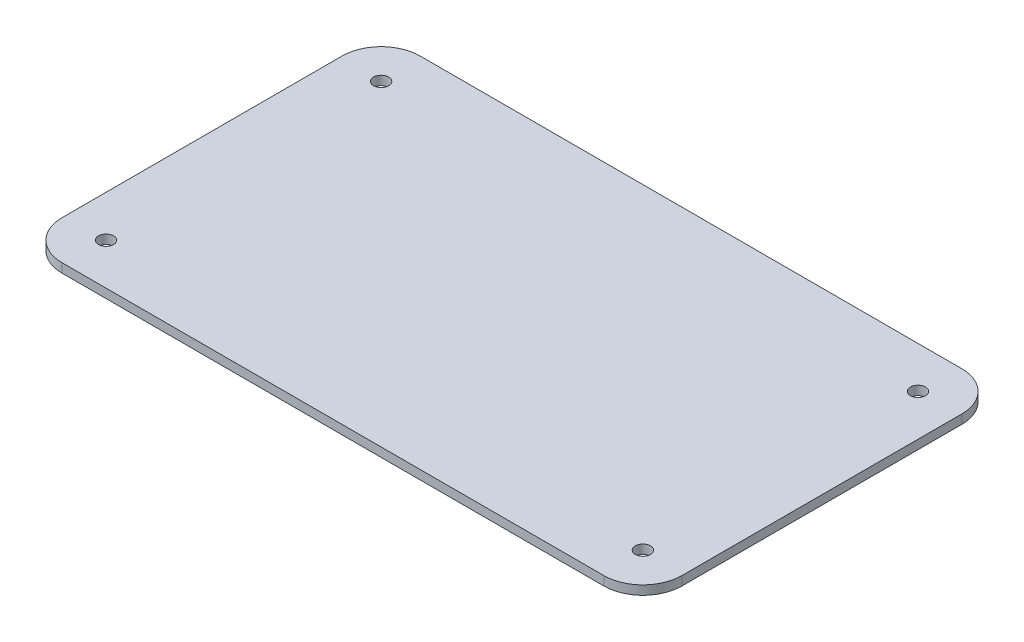
SolidWorks part; units mm, degrees
ref_plane "Front Plane" through (0, 0, 0) normal (0, 0, 1) x (1, 0, 0)
ref_plane "Top Plane" through (0, 0, 0) normal (0, 1, 0) x (1, 0, 0)
ref_plane "Right Plane" through (0, 0, 0) normal (1, 0, 0) x (0, 0, -1)
sketch "Sketch2" plane through (0, 0, 0) normal (0, 1, 0) x (1, 0, 0)
  line L0 (0, 59.325) -> (0, -59.325) construction
  line L1 (-89.75, -59.325) -> (89.75, -59.325)
  line L2 (-102.69, -46.385) -> (-102.69, 46.385)
  line L3 (-89.75, 59.325) -> (89.75, 59.325)
  line L4 (102.69, -46.385) -> (102.69, 46.385)
  line L5 (-102.69, -59.325) -> (102.69, 59.325) construction
  line L6 (-102.69, 59.325) -> (102.69, -59.325) construction
  line L7 (-102.69, 0) -> (102.69, 0) construction
  arc A0 (89.75, 59.325) -> (102.69, 46.385) centre (89.75, 46.385) cw
  arc A1 (89.75, -59.325) -> (102.69, -46.385) centre (89.75, -46.385) ccw
  arc A2 (-89.75, -59.325) -> (-102.69, -46.385) centre (-89.75, -46.385) cw
  arc A3 (-102.69, 46.385) -> (-89.75, 59.325) centre (-89.75, 46.385) cw
  circle A4 centre (-88.94, 45.575) radius 2.5
  circle A5 centre (88.94, 45.575) radius 2.5
  circle A6 centre (88.94, -45.575) radius 2.5
  circle A7 centre (-88.94, -45.575) radius 2.5
  point P0 (0, 0)
  dimension "D3" = 12.94
  dimension "D4" = 5
  dimension "D1" = 205.38
  dimension "D2" = 118.65
  dimension "D5" = 13.75
  dimension "D6" = 13.75
extrude "Boss-Extrude1" add sketch "Sketch2" along normal blind 3
